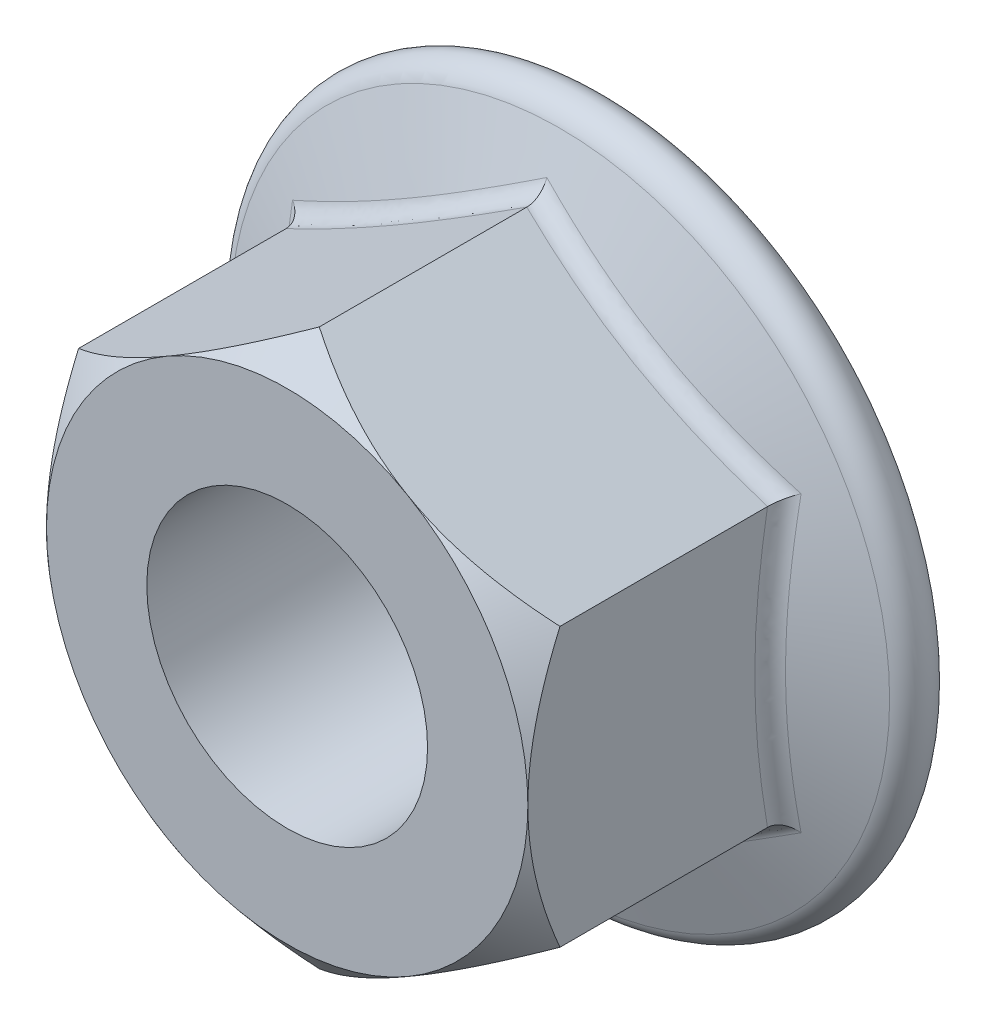
SolidWorks part; units mm, degrees
extrude "BaseNut" add sketch "BaseNutSke" against normal blind 16
sketch "BaseNutSke" plane through (0, 0, 0) normal (0, 0, 1) x (1, 0, 0)
  line L6 (12, 6.9282) -> (12, -6.9282)
  line L7 (-12, 6.9282) -> (-12, -6.9282)
  line L8 (12, 6.9282) -> (0, 13.8564)
  line L9 (0, 13.8564) -> (-12, 6.9282)
  line L10 (-12, -6.9282) -> (0, -13.8564)
  line L11 (0, -13.8564) -> (12, -6.9282)
  circle A0 centre (0, 0) radius 7
  dimension "Tap_drill" = 14
  dimension "Width_flats" = 24
  dimension "D2" = 12
  dimension "D3" = 12
  dimension "D1" = 120
  dimension "D4" = 12
cosmetic thread "ThreadCosmetic" parameters "Thread_major"=16
pattern_linear "ThdSchPat" [suppressed]
revolve "ThreadSchematic" [suppressed] cut sketch "ThdSchSke" angle 360 about L6
sketch "ThdSchSke" plane through (0, 0, 0) normal (0, 1, 0) x (1, 0, 0)
  line L0 (-8, 0.0254) -> (-7, 0.7256)
  line L1 (-7, 0.7256) -> (-3.5, 0.7256)
  line L2 (-3.5, 0.7256) -> (-3.5, -0.6748)
  line L3 (-3.5, -0.6748) -> (-7, -0.6748)
  line L4 (-7, -0.6748) -> (-8, 0.0254)
  line L5 (-3.175, 2) -> (3.175, 2) construction
  line L6 (0, 2) -> (0, -2.9874) construction
  line L7 (0, 16) -> (0, 0) construction
  dimension "Thread_major" = 16
  dimension "SideAngle" = 55
  dimension "D1" = 0.0254
material "Сталь 20 ГОСТ 535-88"
ref_plane "Plane1" through (0, 0, 0) normal (0, 0, 1) x (1, 0, 0)
ref_plane "Plane2" through (0, 0, 0) normal (0, 1, 0) x (1, 0, 0)
ref_plane "Plane3" through (0, 0, 0) normal (1, 0, 0) x (0, 0, -1)
other "Configuration Table"
sketch "Sketch6" plane through (0, 0, 0) normal (1, 0, 0) x (0, 0, -1)
  line L0 (10.1656, 7) -> (13.6, 16.4359)
  line L1 (16, 7) -> (16, 16.0127)
  line L2 (13.6, 32.2909) -> (13.6, 16.4359) construction
  line L3 (23.7075, 17.25) -> (19.5103, 17.25) construction
  line L4 (16, 7) -> (10.1656, 7)
  line L5 (23.7075, -17.25) -> (19.5103, -17.25) construction
  line L6 (16, 6.9282) -> (16, 13.8564) construction
  line L7 (0, 0) -> (32.9582, 0) construction
  line L8 (16, -7) -> (10.1656, -7) construction
  line L9 (16, 0) -> (0, 0) construction
  arc A0 (16, 16.0127) -> (13.6, 16.4359) centre (14.7627, 16.0127) ccw
  dimension "Flange_thickness" = 2.4
  dimension "Flange_dia" = 34.5
  dimension "D2" = 20
  dimension "D1" = 14
revolve "Flange" add sketch "Sketch6" angle 360 about L7
sketch "Sketch3" plane through (0, 0, 0) normal (1, 0, 0) x (0, 0, -1)
  line L0 (16, 12) -> (14.4, 13.8564) construction
  line L1 (14.4, 13.8564) -> (14.4, 26.5564) construction
  line L2 (14.4, 26.5564) -> (28.7, 26.5564) construction
  line L3 (28.7, 26.5564) -> (28.7, 12) construction
  line L4 (28.7, 12) -> (16, 12) construction
  line L5 (16, 6.9282) -> (16, 13.8564) construction
  line L6 (12.6612, 13.8564) -> (0, 13.8564) construction
  line L7 (0, 0) -> (38.6776, 0) construction
  line L8 (16, 0) -> (0, 0) construction
  line L9 (8, 13.8564) -> (8, 44.222) construction
  line L10 (1.6, 26.5564) -> (-12.7, 26.5564)
  line L11 (-12.7, 26.5564) -> (-12.7, 12)
  line L12 (-12.7, 12) -> (0, 12)
  line L13 (0, 12) -> (1.6, 13.8564)
  line L14 (1.6, 13.8564) -> (1.6, 26.5564)
  line L16 (12.6612, 13.8564) -> (0, 13.8564) construction
  dimension "D1" = 12
  dimension "D4" = 12.7
  dimension "D3" = 12.7
  dimension "D5" = 8
revolve "Double-Chamfer" cut sketch "Sketch3" angle 360 about L7
fillet "FlangeFillet" radius 0.96 6 edges
sketch "Sketch5" plane through (0, 0, 0) normal (1, 0, 0) x (0, 0, -1)
  line L0 (41.3492, 8) -> (40.579, 6.9)
  line L1 (41.4, 8) -> (41.3492, 8)
  line L2 (41.4, 8) -> (41.4, 6.9)
  line L3 (41.4, 6.9) -> (40.579, 6.9)
  line L6 (-50.8, 8) -> (-50.7492, 8)
  line L7 (-50.7492, 8) -> (-49.979, 6.9)
  line L9 (-49.979, 6.9) -> (-50.8, 6.9)
  line L10 (-50.8, 6.9) -> (-50.8, 8)
  line L11 (25.0375, 0) -> (38.388, 0) construction
  line L12 (16, 0) -> (0, 0) construction
  dimension "D1" = 35
  dimension "ThreadMajor" = 8
  dimension "Offset1" = 41.4
revolve "EndChamfer" [suppressed] cut sketch "Sketch5" angle 360 about L11
equation "\"D2@BaseNutSke\" = \"Width_flats@BaseNutSke\" / 2"
equation "\"D3@BaseNutSke\" = \"Width_flats@BaseNutSke\" / 2"
equation "\"D1@Sketch3\" = \"Width_flats@BaseNutSke\" /2"
equation "\"D2@Sketch3\" = \"Thread_major@ThreadCosmetic\" *.1"
equation "\"D4@BaseNutSke\" = \"D3@BaseNutSke\""
equation "\"Thread_major@ThdSchSke\" = \"Thread_major@ThreadCosmetic\""
equation "\"Tap_Drill@ThdSchSke\" = \"Tap_drill@BaseNutSke\""
equation "\"OverCut@ThdSchSke\" = \"Tap_Drill@ThdSchSke\" * 0.5"
equation "\"Num_threads@ThdSchPat\" = int(  ( \"Thickness@BaseNut\" - 0.0508 ) / \"Advance@ThdSchSke\" + 0.999 )  + 1"
equation "\"Advance@ThdSchPat\" = ( \"Thickness@BaseNut\" - 0.0508 ) /  (\"Num_threads@ThdSchPat\" - 1) 'relax it"
equation "' \"Num_threads@ThdSchPat\" = \"Num_threads@ThdSchPat\" - sgn( \"Num_threads@ThdSchPat\" - 1) '---chamfered tips only---"
equation "\"ThreadMajor@Sketch5\" = \"Thread_major@ThreadCosmetic\" * 0.5"
equation "\"ChamferDepth@Sketch5\" = (\"Thread_major@ThreadCosmetic\" - \"Tap_drill@BaseNutSke\") * 0.55"
equation "\"Offset1@Sketch5\" = \"Thickness@BaseNut\" + 0.0254"
equation "\"Offset2@Sketch5\" = \"Offset1@Sketch5\" + 0.0508"
equation "\"D1@Sketch6\" = \"Tap_drill@BaseNutSke\""
equation "\"D5@Sketch3\" = \"Thickness@BaseNut\" / 2"
